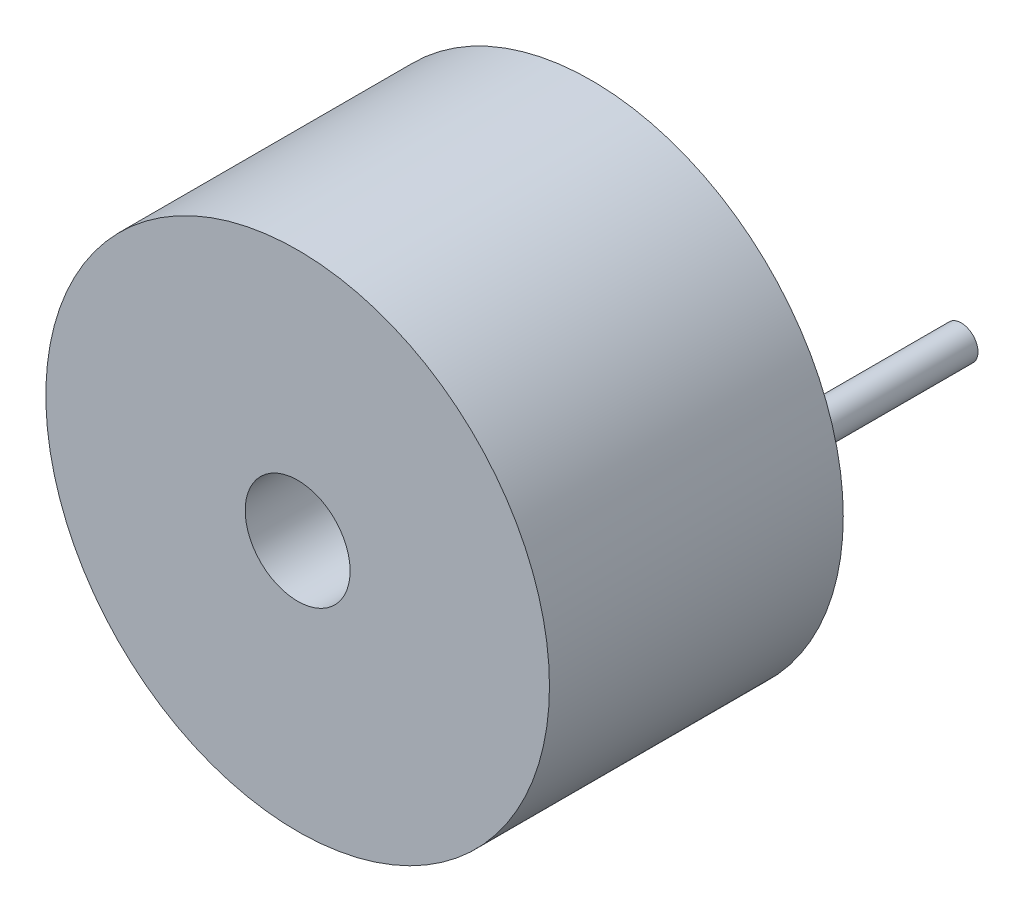
SolidWorks part; units mm, degrees
ref_plane "前视基准面" through (0, 0, 0) normal (0, 0, 1) x (1, 0, 0)
ref_plane "上视基准面" through (0, 0, 0) normal (0, 1, 0) x (1, 0, 0)
ref_plane "右视基准面" through (0, 0, 0) normal (1, 0, 0) x (0, 0, -1)
sketch "草图1" plane through (0, 0, 0) normal (0, 0, 1) x (1, 0, 0)
  circle A0 centre (0, 0) radius 6
  dimension "D1" = 12
extrude "拉伸1" add sketch "草图1" along normal blind 7
sketch "草图2" plane through (0, 0, 0) normal (0, 0, -1) x (-1, 0, 0)
  line L0 (6.6594, 0) -> (-8.124, 0) construction
  line L1 (0, 6.6022) -> (0, -6.3733) construction
  circle A0 centre (-3.81, 0) radius 0.4
  circle A1 centre (3.81, 0) radius 0.4
  dimension "D1" = 0.8
  dimension "D2" = 7.62
extrude "拉伸2" add sketch "草图2" along normal blind 5
sketch "草图3" plane through (0, 0, 7) normal (0, 0, 1) x (1, 0, 0)
  circle A0 centre (0, 0) radius 1.25
  dimension "D1" = 2.5
extrude "切除-拉伸1" cut sketch "草图3" against normal blind 5
